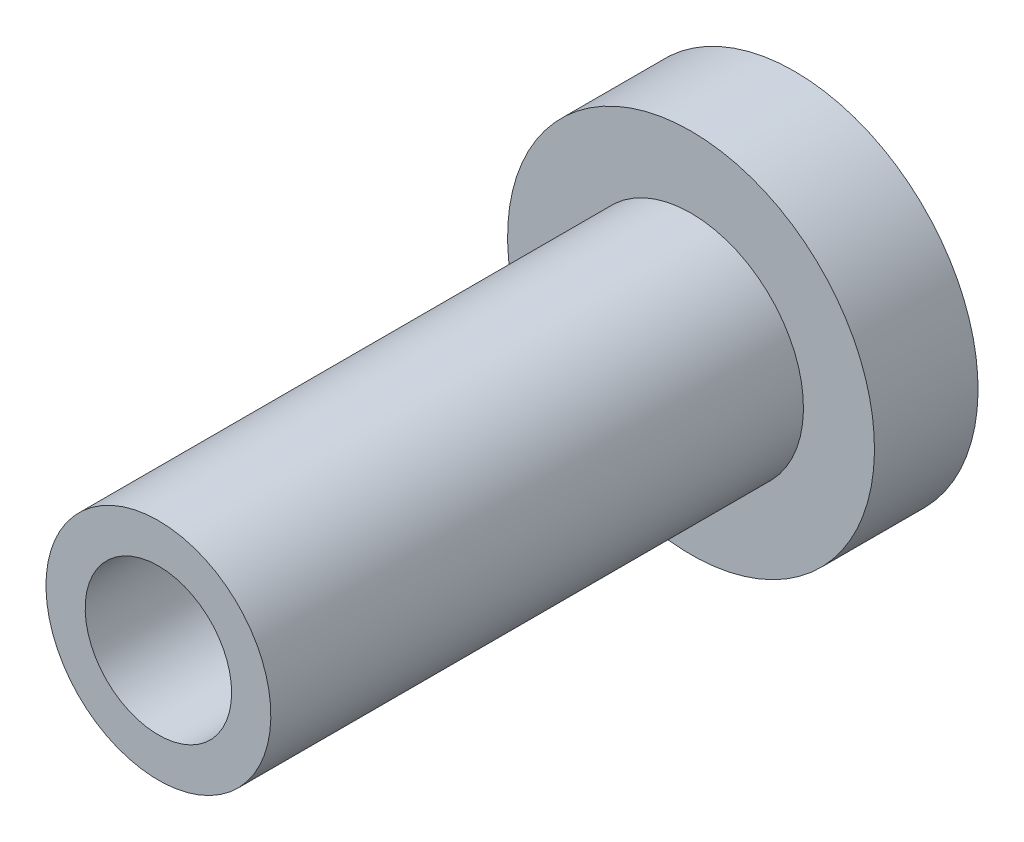
SolidWorks part; units mm, degrees
ref_plane "Front Plane" through (0, 0, 0) normal (0, 0, 1) x (1, 0, 0)
ref_plane "Top Plane" through (0, 0, 0) normal (0, 1, 0) x (1, 0, 0)
ref_plane "Right Plane" through (0, 0, 0) normal (1, 0, 0) x (0, 0, -1)
sketch "Sketch1" plane through (0, 0, 0) normal (1, 0, 0) x (0, 0, -1)
  line L0 (0, 0) -> (-21.5, 0)
  line L1 (-21.5, 0) -> (-21.5, -3.8)
  line L2 (-21.5, -3.8) -> (-3.5, -3.8)
  line L3 (-3.5, -3.8) -> (-3.5, -6.2)
  line L4 (-3.5, -6.2) -> (0, -6.2)
  line L5 (0, -6.2) -> (0, 0)
  dimension "D1" = 18
  dimension "D2" = 3.5
  dimension "D3" = 3.8
  dimension "D4" = 6.2
revolve "Revolve1" add sketch "Sketch1" angle 360 about L0
ref_plane "Plane1" through (3.8, 0, 0) normal (1, 0, 0) x (0, 0, -1)
sketch "Sketch3" plane through (0, 0, 21.5) normal (0, 0, 1) x (1, 0, 0)
  circle A0 centre (0, 0) radius 2.475
  dimension "D1" = 4.95
extrude "Cut-Extrude1" cut sketch "Sketch3" against normal through all both and the other way through all
